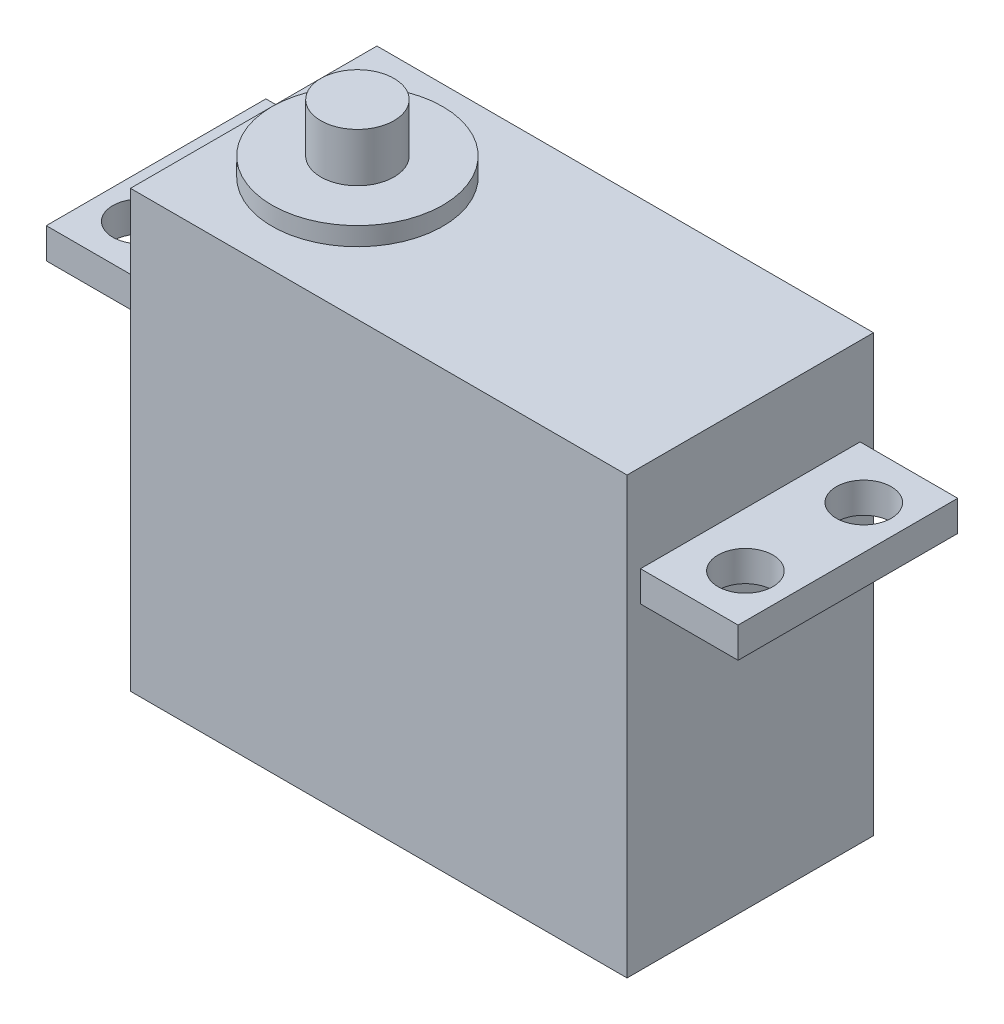
SolidWorks part; units mm, degrees
ref_plane "Vorne" through (0, 0, 0) normal (0, 0, 1) x (1, 0, 0)
ref_plane "Oben" through (0, 0, 0) normal (0, 1, 0) x (1, 0, 0)
ref_plane "Rechts" through (0, 0, 0) normal (1, 0, 0) x (0, 0, -1)
sketch "Skizze1" plane through (0, 0, 0) normal (0, 0, 1) x (1, 0, 0)
  line L1 (0, 0) -> (40.7, 0)
  line L2 (0, 0) -> (0, 35.7)
  line L3 (0, 35.7) -> (40.7, 35.7)
  line L4 (40.7, 0) -> (40.7, 35.7)
  dimension "D1" = 40.7
  dimension "D2" = 35.7
extrude "Aufsatz-Linear austragen1" add sketch "Skizze1" along normal blind 20.2
sketch "Skizze2" plane through (40.7, 0, 0) normal (1, 0, 0) x (0, 0, -1)
  line L0 (-20.2, 0) -> (0, 0) construction
  line L1 (-19.1, 28.5) -> (-1.1, 28.5)
  line L2 (-19.1, 28.5) -> (-19.1, 26)
  line L3 (-19.1, 26) -> (-1.1, 26)
  line L4 (-1.1, 28.5) -> (-1.1, 26)
  line L5 (-20.2, 0) -> (-20.2, 35.7) construction
  dimension "D1" = 26
  dimension "D2" = 18
  dimension "D3" = 1.1
  dimension "D4" = 2.5
extrude "Aufsatz-Linear austragen2" add sketch "Skizze2" along normal blind 8 and the other way blind 48.7
sketch "Skizze3" plane through (0, 28.5, 0) normal (0, 1, 0) x (1, 0, 0)
  line L0 (40.7, -1.1) -> (48.7, -1.1) construction
  line L1 (40.7, -19.1) -> (48.7, -19.1) construction
  line L2 (48.7, -1.1) -> (48.7, -19.1) construction
  line L3 (-8, -1.1) -> (-8, -19.1) construction
  line L4 (-8, -1.1) -> (0, -1.1) construction
  line L5 (-8, -19.1) -> (0, -19.1) construction
  circle A0 centre (45.15, -5.25) radius 2.25
  circle A1 centre (45.15, -14.95) radius 2.25
  circle A2 centre (-4.45, -5.25) radius 2.25
  circle A3 centre (-4.45, -14.95) radius 2.25
  dimension "D1" = 4.5
  dimension "D2" = 4.5
  dimension "D3" = 4.15
  dimension "D4" = 4.15
  dimension "D5" = 3.55
  dimension "D6" = 3.55
  dimension "D7" = 3.55
  dimension "D8" = 3.55
  dimension "D9" = 4.5
  dimension "D10" = 4.5
  dimension "D11" = 4.15
  dimension "D12" = 4.15
extrude "Schnitt-Linear austragen1" cut sketch "Skizze3" against normal blind 8
sketch "Skizze4" plane through (0, 35.7, 0) normal (0, 1, 0) x (1, 0, 0)
  line L0 (40.7, 0) -> (0, 0) construction
  line L3 (0, -1.1) -> (0, -19.1) construction
  circle A0 centre (8.5, -10.1) radius 7
  dimension "D1" = 10.1
  dimension "D2" = 14
  dimension "D3" = 8.5
extrude "Aufsatz-Linear austragen3" add sketch "Skizze4" along normal blind 1.5
sketch "Skizze5" plane through (0, 37.2, 0) normal (0, 1, 0) x (1, 0, 0)
  circle A0 centre (8.5, -10.1) radius 3
  dimension "D1" = 6
extrude "Aufsatz-Linear austragen4" add sketch "Skizze5" along normal blind 4
sketch "Skizze6" plane through (0, 0, 0) normal (-1, 0, 0) x (0, 0, 1)
  line L1 (7.1, 4.5) -> (13.1, 4.5)
  line L2 (7.1, 4.5) -> (7.1, 1)
  line L3 (7.1, 1) -> (13.1, 1)
  line L4 (13.1, 4.5) -> (13.1, 1)
  line L5 (20.2, 35.7) -> (20.2, 0) construction
  line L6 (20.2, 0) -> (0, 0) construction
  point P6 (10.1, 4.5)
  dimension "D1" = 10.1
  dimension "D2" = 6
  dimension "D3" = 3.5
  dimension "D4" = 1
extrude "Aufsatz-Linear austragen5" add sketch "Skizze6" along normal blind 4
